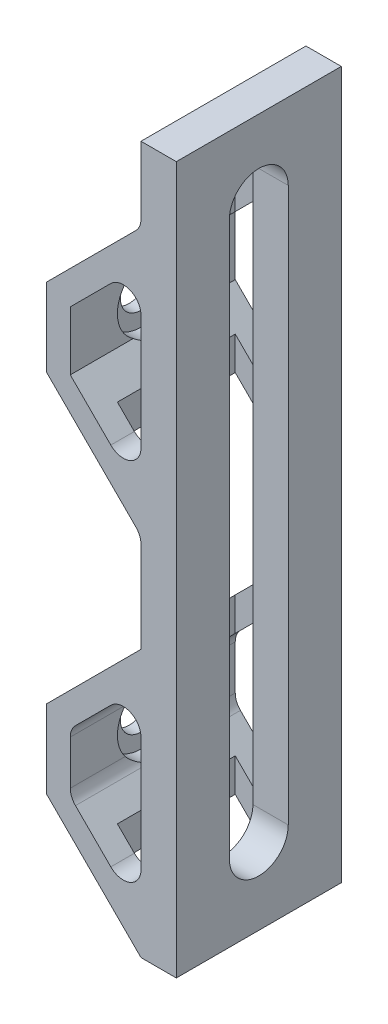
SolidWorks part; units mm, degrees
ref_plane "Front Plane" through (0, 0, 0) normal (1, 0, 0) x (0, 1, 0)
ref_plane "Top Plane" through (0, 0, 0) normal (0, 0, 1) x (0, 1, 0)
ref_plane "Right Plane" through (0, 0, 0) normal (0, 1, 0) x (-1, 0, 0)
sketch "Sketch4" plane through (0, 0, 0) normal (1, 0, 0) x (0, 1, 0)
  line L0 (0, 7) -> (60, 7) construction
  line L1 (0, 0) -> (60, 0)
  line L2 (0, 0) -> (0, 14)
  line L3 (0, 14) -> (60, 14)
  line L4 (60, 0) -> (60, 14)
  line L5 (30, 14) -> (30, 0) construction
  line L6 (6.5, 7) -> (53.5, 7) construction
  line L7 (6.5, 9.5) -> (53.5, 9.5)
  line L8 (6.5, 4.5) -> (53.5, 4.5)
  arc A0 (6.5, 9.5) -> (6.5, 4.5) centre (6.5, 7) ccw
  arc A1 (53.5, 4.5) -> (53.5, 9.5) centre (53.5, 7) ccw
  point P11 (30, 7)
  dimension "D4" = 4
  dimension "D1" = 14
  dimension "D2" = 60
  dimension "D3" = 5
extrude "Boss-Extrude2" add sketch "Sketch4" along normal blind 3
sketch "Sketch6" plane through (0, 0, 0) normal (0, 0, -1) x (1, 0, 0)
  line L0 (0, -2.8284) -> (-6, -8.8284)
  line L1 (0, 0) -> (0, -60) construction
  line L2 (-6, -8.8284) -> (-6, -13.8284)
  line L3 (-6, -13.8284) -> (0, -19.8284)
  line L4 (0, 0) -> (-8, -8)
  line L5 (-8, -8) -> (-8, -14.6569)
  line L6 (-8, -14.6569) -> (0, -22.6569)
  line L7 (0, -19.8284) -> (0, -22.6569)
  line L8 (0, -2.8284) -> (0, 0)
  line L9 (3, 0) -> (0, 0) construction
  line L10 (0, -33.8284) -> (-6, -39.8284)
  line L11 (-6, -39.8284) -> (-6, -44.8284)
  line L12 (-6, -44.8284) -> (0, -50.8284)
  line L13 (0, -31) -> (-8, -39)
  line L14 (-8, -39) -> (-8, -45.6569)
  line L15 (-8, -45.6569) -> (0, -53.6569)
  line L16 (0, -50.8284) -> (0, -53.6569)
  line L17 (0, -33.8284) -> (0, -31)
  dimension "D1" = 2
  dimension "D2" = 2
  dimension "D3" = 5
  dimension "D5" = 6
  dimension "D6" = 2
  dimension "D4" = 2
extrude "Boss-Extrude3" add sketch "Sketch6" against normal up to surface (14 mm away) up to face at (1.5, 30, 14)
sketch "Sketch7" plane through (0, 60, 0) normal (0, 1, 0) x (-1, 0, 0)
  line L7 (-3, 7) -> (8, 7) construction
  line L9 (-3, 0) -> (-3, 14) construction
  line L12 (8, 14) -> (8, 0) construction
  line L14 (0, 9.4951) -> (0, 4.5049) construction
  line L15 (0, 12) -> (4, 12)
  line L16 (0, 12) -> (0, 2)
  line L17 (0, 2) -> (4, 2)
  line L18 (4, 12) -> (4, 2)
  line L19 (0, 0) -> (0, 14) construction
  point P14 (4, 7)
  dimension "D1" = 10
  dimension "D2" = 4
extrude "Cut-Extrude2" cut sketch "Sketch7" against normal through all
sketch "Sketch8" plane through (-6, 0, 0) normal (1, 0, 0) x (0, 1, 0)
  line L0 (43.0021, 7) -> (32.3453, 7) construction
  line L1 (8.8284, 6.2693) -> (13.8284, 6.2693) construction
  line L2 (8.8284, 14) -> (8.8284, 0) construction
  line L3 (42.3284, 7) -> (42.3284, 9.5) construction
  line L4 (53.5, 9.5) -> (6.5, 9.5) construction
  line L5 (0, 14) -> (0, 0) construction
  line L6 (13.8284, 14) -> (13.8284, 0) construction
  circle A0 centre (42.3284, 7) radius 1.75
  circle A1 centre (11.3284, 7) radius 1.75
  point P16 (0, 7)
  point P19 (11.3284, 6.2693)
  dimension "D2" = 3.5
  dimension "D1" = 31
extrude "Cut-Extrude3" cut sketch "Sketch8" against normal through all
sketch "Sketch9" plane through (-6, 0, 0) normal (1, 0, 0) x (0, 1, 0)
  line L0 (11.3284, 7) -> (42.3284, 7) construction
  line L1 (26.8284, 7) -> (26.8284, 4.5) construction
  line L2 (6.5, 4.5) -> (53.5, 4.5) construction
  circle A0 centre (11.3284, 7) radius 3
  circle A1 centre (42.3284, 7) radius 3
  dimension "D1" = 6
extrude "Cut-Extrude4" cut sketch "Sketch9" against normal blind 1 and the other way up to next
fillet "Fillet1" radius 1.5 15 edges at (0, 53.6569, 1) (0, 53.6569, 13) (0, 33.8284, 13) (0, 50.8284, 13) (0, 31, 13) (0, 50.8284, 1) (0, 33.8284, 1) (0, 2.8284, 13) (0, 19.8284, 13) (0, 19.8284, 1) (0, 2.8284, 1) (-6, 13.8284, 11.3292) (-6, 8.8284, 11.3292) (-6, 8.8284, 2.6708) (-6, 13.8284, 2.6708)
